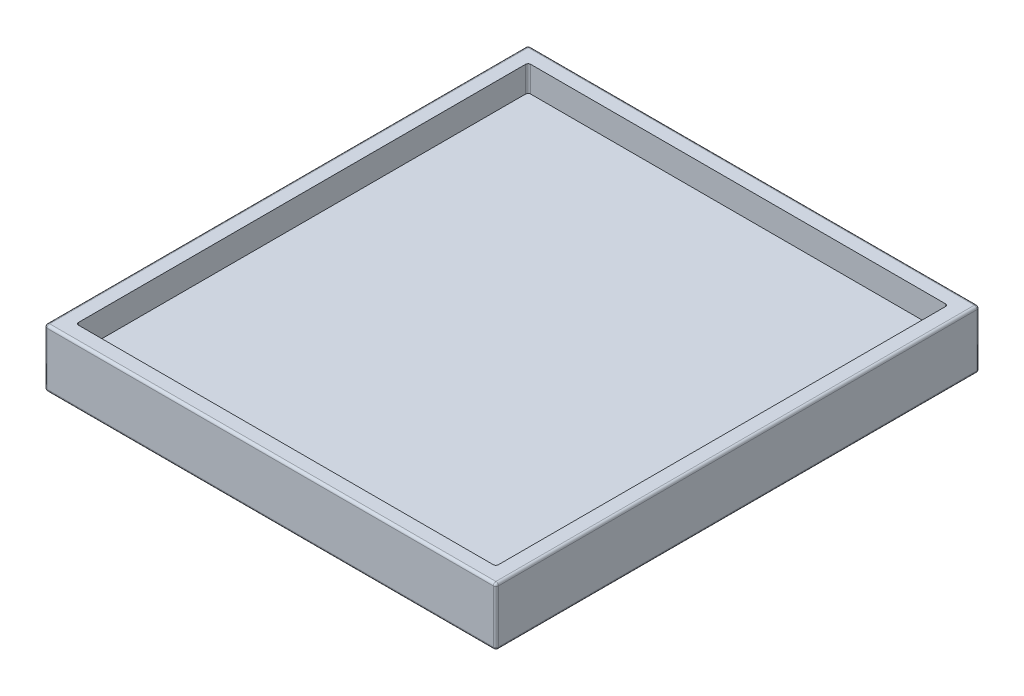
SolidWorks part; units mm, degrees
ref_plane "Front Plane" through (0, 0, 0) normal (0, 0, 1) x (1, 0, 0)
ref_plane "Top Plane" through (0, 0, 0) normal (0, 1, 0) x (1, 0, 0)
ref_plane "Right Plane" through (0, 0, 0) normal (1, 0, 0) x (0, 0, -1)
sketch "Sketch1" plane through (0, 0, 0) normal (0, 1, 0) x (1, 0, 0)
  line L1 (0, 0) -> (70, 0)
  line L2 (0, 0) -> (0, 75)
  line L3 (0, 75) -> (70, 75)
  line L4 (70, 0) -> (70, 75)
  dimension "D1" = 75
  dimension "D2" = 70
extrude "Boss-Extrude1" add sketch "Sketch1" along normal blind 9
sketch "Sketch2" plane through (0, 9, 0) normal (0, 1, 0) x (1, 0, 0)
  line L0 (35, 75) -> (35, 0) construction
  line L1 (70, 75) -> (0, 75) construction
  line L2 (0, 0) -> (70, 0) construction
  line L4 (2.45, 2.45) -> (67.55, 2.45)
  line L5 (2.45, 2.45) -> (2.45, 72.55)
  line L6 (2.45, 72.55) -> (67.55, 72.55)
  line L7 (67.55, 2.45) -> (67.55, 72.55)
  line L8 (2.45, 2.45) -> (67.55, 72.55) construction
  line L9 (2.45, 72.55) -> (67.55, 2.45) construction
  point P6 (35, 37.5)
  dimension "D1" = 70.1
  dimension "D2" = 65.1
extrude "Cut-Extrude1" cut sketch "Sketch2" against normal offset from surface (4 mm away) 5 up to face at (35, 0, -37.5)
sketch "Sketch4" plane through (0, 0, 0) normal (0, -1, 0) x (1, 0, 0)
  line L0 (35, 0) -> (35, -75) construction
  line L1 (0, 0) -> (70, 0) construction
  line L2 (70, -75) -> (0, -75) construction
  circle A0 centre (17.5, -54) radius 2.5
  circle A1 centre (52.5, -54) radius 2.5
  dimension "D1" = 5
  dimension "D2" = 35
  dimension "D3" = 54
extrude "Boss-Extrude3" add sketch "Sketch4" along normal blind 7.5
fillet "Fillet1" radius 0.4 20 edges at (2.45, 7, -2.45) (67.55, 7, -2.45) (67.55, 7, -72.55) (2.45, 7, -72.55) (35, 0, 0) (70, 0, -37.5) (35, 0, -75) (0, 9, -37.5) (35, 9, 0) (70, 9, -37.5) (35, 9, -75) (0, 0, -37.5) (0, 4.5, -75) (70, 4.5, -75) (70, 4.5, 0) (0, 4.5, 0) (52.5, 0, -51.5) (17.5, 0, -56.5) (52.5, -7.5, -51.5) (17.5, -7.5, -56.5)
